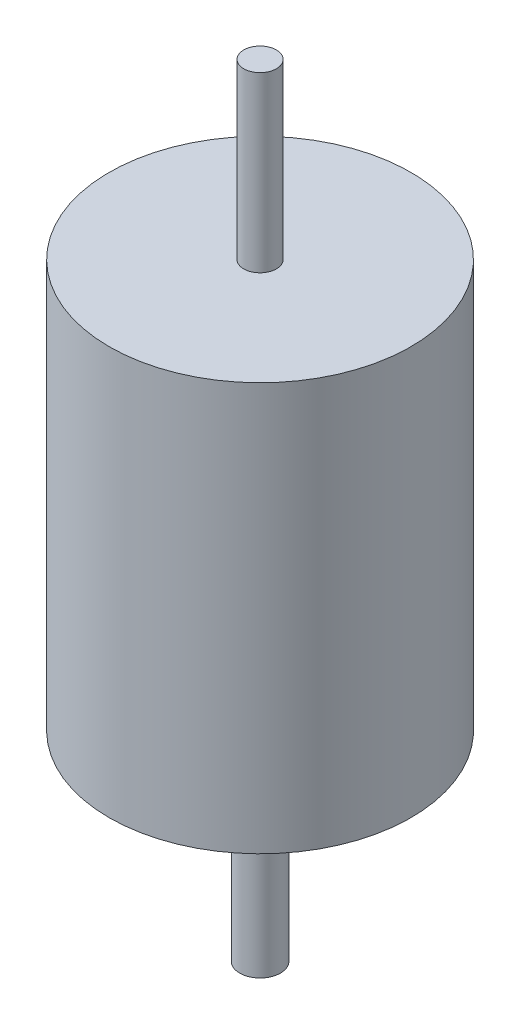
SolidWorks part; units mm, degrees
ref_plane "Front Plane" through (0, 0, 0) normal (0, 0, 1) x (1, 0, 0)
ref_plane "Top Plane" through (0, 0, 0) normal (0, 1, 0) x (1, 0, 0)
ref_plane "Right Plane" through (0, 0, 0) normal (1, 0, 0) x (0, 0, -1)
sketch "Sketch1" plane through (0, 0, 0) normal (0, 1, 0) x (1, 0, 0)
  circle A0 centre (0, 0) radius 7.4
  dimension "D1" = 14.8
extrude "Boss-Extrude1" add sketch "Sketch1" along normal blind 20
sketch "Sketch2" plane through (0, 20, 0) normal (0, 1, 0) x (1, 0, 0)
  circle A0 centre (0, 0) radius 0.8
  dimension "D1" = 1.6
extrude "Boss-Extrude2" add sketch "Sketch2" along normal blind 8.5
sketch "Sketch3" plane through (0, 0, 0) normal (0, -1, 0) x (1, 0, 0)
  circle A0 centre (0, 0) radius 1
  dimension "D1" = 2
extrude "Boss-Extrude3" add sketch "Sketch3" along normal blind 9.8
